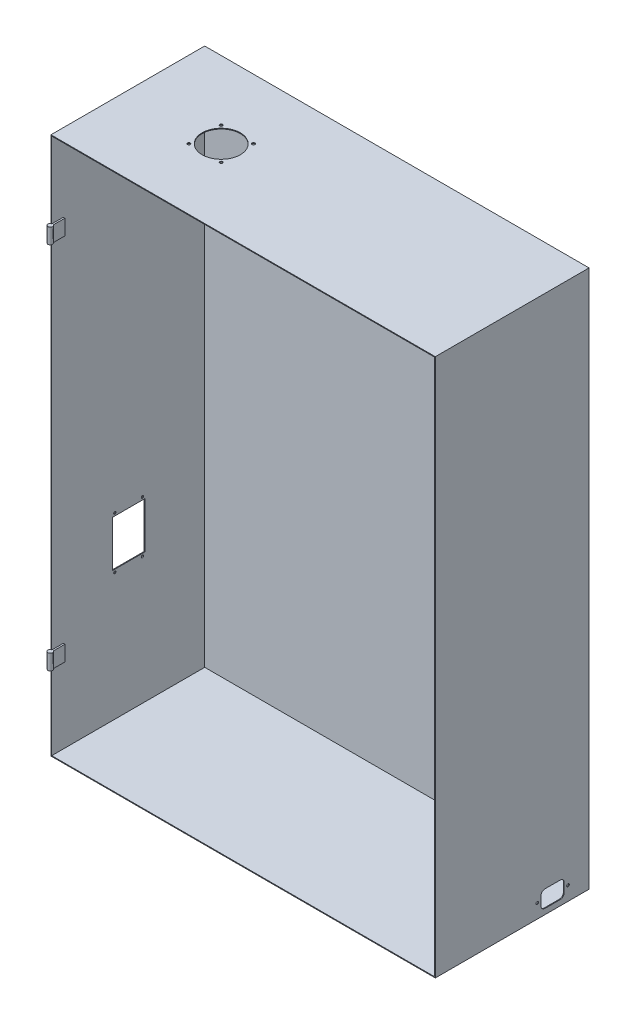
SolidWorks part; units mm, degrees
material "Acero inoxidable al cromo"
ref_plane "Alzado" through (0, 0, 0) normal (0, 0, 1) x (1, 0, 0)
ref_plane "Planta" through (0, 0, 0) normal (0, 1, 0) x (1, 0, 0)
ref_plane "Vista lateral" through (0, 0, 0) normal (1, 0, 0) x (0, 0, -1)
sketch "Croquis1" plane through (0, 0, 0) normal (0, 0, 1) x (1, 0, 0)
  line L1 (-250, -350) -> (250, -350)
  line L2 (-250, -350) -> (-250, 350)
  line L3 (-250, 350) -> (250, 350)
  line L4 (250, -350) -> (250, 350)
  line L5 (-250, -350) -> (250, 350) construction
  line L6 (-250, 350) -> (250, -350) construction
  point P0 (0, 0)
  dimension "D1" = 700
  dimension "D2" = 500
extrude "Saliente-Extruir1" add sketch "Croquis1" along normal blind 200
shell "Vaciado1" thickness 1
sketch "Croquis2" plane through (-249, 0, 0) normal (1, 0, 0) x (0, 0, -1)
  line L0 (-200, 349) -> (-200, -349) construction
  line L1 (-200, 250) -> (-185, 250)
  line L2 (-200, 250) -> (-200, 230)
  line L3 (-200, 230) -> (-185, 230)
  line L4 (-185, 250) -> (-185, 230)
  line L5 (-200, 350) -> (0, 350) construction
  line L6 (-200, -230) -> (-185, -230)
  line L7 (-200, -230) -> (-200, -250)
  line L8 (-200, -250) -> (-185, -250)
  line L9 (-185, -230) -> (-185, -250)
  line L10 (-200, -350) -> (0, -350) construction
  dimension "D1" = 20
  dimension "D2" = 15
  dimension "D3" = 20
  dimension "D4" = 15
  dimension "D5" = 100
  dimension "D6" = 100
extrude "Saliente-Extruir2" add sketch "Croquis2" along normal blind 2
sketch "Croquis3" plane through (0, -250, 0) normal (0, -1, 0) x (1, 0, 0)
  line L0 (-250, 200) -> (-250, 0) construction
  line L1 (-250, 200) -> (250, 200) construction
  circle A0 centre (-248.5, 202.5) radius 3
  dimension "D1" = 6
  dimension "D2" = 1.5
  dimension "D3" = 2.5
extrude "Saliente-Extruir3" add sketch "Croquis3" against normal up to vertex
sketch "Croquis4" plane through (0, 230, 0) normal (0, -1, 0) x (1, 0, 0)
  line L0 (-250, 199.9019) -> (-247, 199.9019)
  arc A0 (-247, 199.9019) -> (-250, 199.9019) centre (-248.5, 202.5) ccw construction
  arc A1 (-247, 199.9019) -> (-250, 199.9019) centre (-248.5, 202.5) ccw
extrude "Saliente-Extruir4" add sketch "Croquis4" against normal up to vertex contours A1 L0
sketch "Croquis5" plane through (-249, 0, 0) normal (1, 0, 0) x (0, 0, -1)
  line L0 (-200, -350) -> (0, -350) construction
  line L1 (-121, -120) -> (-79, -120)
  line L2 (-121, -120) -> (-121, -180)
  line L3 (-121, -180) -> (-79, -180)
  line L4 (-79, -120) -> (-79, -180)
  line L5 (-121, -120) -> (-79, -180) construction
  line L6 (-121, -180) -> (-79, -120) construction
  line L7 (0, 350) -> (0, -350) construction
  point P0 (-100, -150)
  dimension "D1" = 60
  dimension "D2" = 42
  dimension "D3" = 100
  dimension "D4" = 200
extrude "Cortar-Extruir1" cut sketch "Croquis5" against normal blind 10
sketch "Croquis6" plane through (-249, 0, 0) normal (1, 0, 0) x (0, 0, -1)
  line L14 (-204.9846, 349) -> (-205.9842, 348)
  line L15 (-205.9842, 348) -> (-703.7777, 348)
  line L16 (-703.7777, 348) -> (-703.7777, -350)
  line L17 (-703.7777, -350) -> (-205.9842, -350)
  line L18 (-205.9842, -350) -> (-204.9846, -351)
  line L19 (-204.9846, -351) -> (-204.9846, -231)
  line L20 (-204.9846, -231) -> (-219.9783, -231)
  line L21 (-219.9783, -231) -> (-219.9783, -211)
  line L22 (-219.9783, -211) -> (-204.9846, -211)
  line L23 (-204.9846, -211) -> (-204.9846, 209)
  line L24 (-204.9846, 209) -> (-219.9783, 209)
  line L25 (-219.9783, 209) -> (-219.9783, 229)
  line L26 (-219.9783, 229) -> (-204.9846, 229)
  line L27 (-204.9846, 229) -> (-204.9846, 349)
  line L28 (-204.9846, 349) -> (-205.9842, 348)
  line L29 (-205.9842, 348) -> (-703.7777, 348)
  line L30 (-703.7777, 348) -> (-703.7777, -350)
  line L31 (-703.7777, -350) -> (-205.9842, -350)
  line L32 (-205.9842, -350) -> (-204.9846, -351)
  line L33 (-204.9846, -351) -> (-204.9846, -231)
  line L34 (-204.9846, -231) -> (-219.9783, -231)
  line L35 (-219.9783, -231) -> (-219.9783, -211)
  line L36 (-219.9783, -211) -> (-204.9846, -211)
  line L37 (-204.9846, -211) -> (-204.9846, 209)
  line L38 (-204.9846, 209) -> (-219.9783, 209)
  line L39 (-219.9783, 209) -> (-219.9783, 229)
  line L40 (-219.9783, 229) -> (-204.9846, 229)
  line L41 (-204.9846, 229) -> (-204.9846, 349)
  circle A0 centre (-118.05, -116.5) radius 1.5
  circle A1 centre (-82.05, -116.5) radius 1.5
  circle A2 centre (-82.05, -183.5) radius 1.5
  circle A3 centre (-118.05, -183.5) radius 1.5
  dimension "D1" = 0
extrude "Cortar-Extruir2" cut sketch "Croquis6" against normal blind 10
sketch "Croquis7" plane through (250, 0, 0) normal (1, 0, 0) x (0, 0, -1)
  line L1 (-37.3944, -342.8854) -> (-57.3944, -342.8854)
  line L2 (-32.3944, -337.8854) -> (-32.3944, -325.8854)
  line L3 (-37.3944, -320.8854) -> (-57.3944, -320.8854)
  line L4 (-62.3944, -337.8854) -> (-62.3944, -325.8854)
  line L5 (-32.3944, -342.8854) -> (-62.3944, -320.8854) construction
  line L6 (-32.3944, -320.8854) -> (-62.3944, -342.8854) construction
  arc A0 (-32.3944, -325.8854) -> (-37.3944, -320.8854) centre (-37.3944, -325.8854) ccw
  arc A1 (-37.3944, -342.8854) -> (-32.3944, -337.8854) centre (-37.3944, -337.8854) ccw
  arc A2 (-57.3944, -342.8854) -> (-62.3944, -337.8854) centre (-57.3944, -337.8854) cw
  arc A3 (-57.3944, -320.8854) -> (-62.3944, -325.8854) centre (-57.3944, -325.8854) ccw
  point P0 (-47.3944, -331.8854)
  dimension "D3" = 5
  dimension "D1" = 22
  dimension "D2" = 30
extrude "Cortar-Extruir3" cut sketch "Croquis7" against normal blind 10
sketch "Croquis8" plane through (249, 0, 0) normal (-1, 0, 0) x (0, 0, 1)
  circle A0 centre (27.3944, -331.8854) radius 1.7
  circle A1 centre (67.3944, -331.8854) radius 1.7
extrude "Cortar-Extruir4" cut sketch "Croquis8" against normal blind 10
sketch "Croquis9" plane through (0, 349, 0) normal (0, -1, 0) x (1, 0, 0)
  circle A0 centre (-129.1407, 99.3833) radius 24.815
  circle A1 centre (-150.1407, 120.4233) radius 1.85
  circle A2 centre (-108.1407, 120.4233) radius 1.85
  circle A3 centre (-150.1407, 78.4233) radius 1.85
  circle A4 centre (-108.1407, 78.4233) radius 1.85
extrude "Cortar-Extruir5" cut sketch "Croquis9" against normal blind 10
